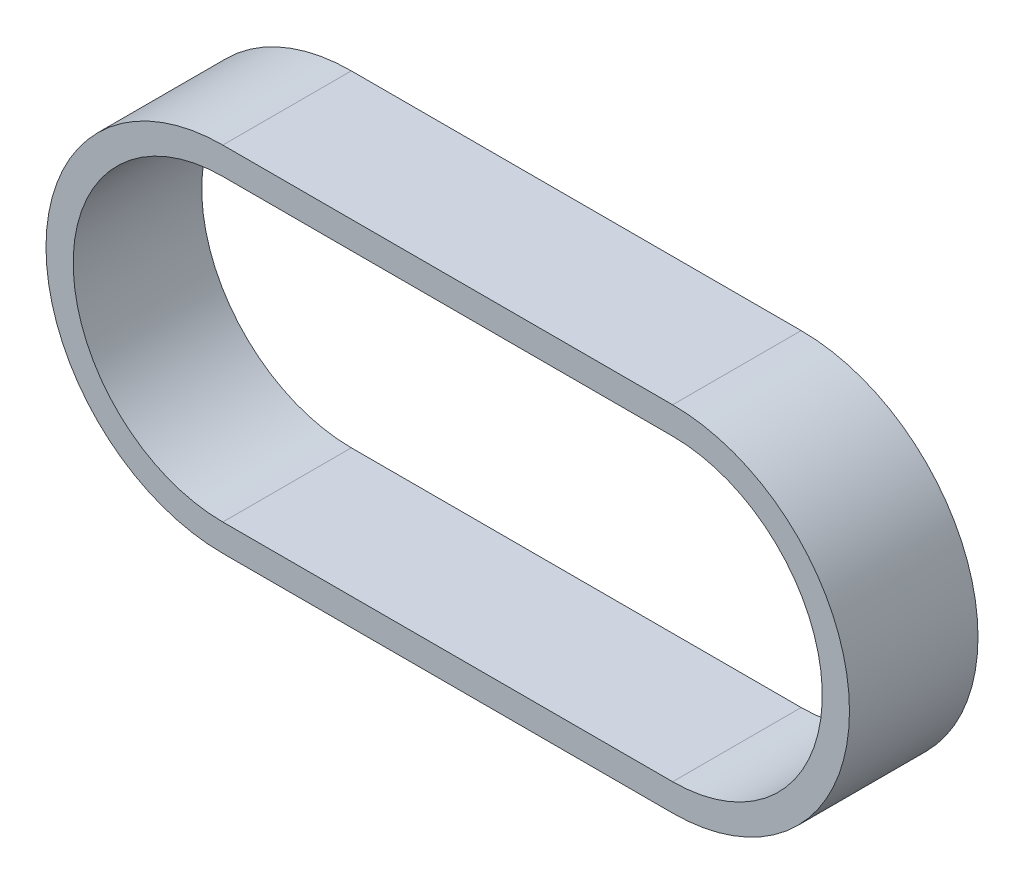
SolidWorks part; units mm, degrees
material "Rubber"
ref_plane "Front Plane" through (0, 0, 0) normal (0, 0, 1) x (1, 0, 0)
ref_plane "Top Plane" through (0, 0, 0) normal (0, 1, 0) x (1, 0, 0)
ref_plane "Right Plane" through (0, 0, 0) normal (1, 0, 0) x (0, 0, -1)
sketch "Sketch1" plane through (0, 0, 0) normal (0, 0, 1) x (1, 0, 0)
  line L0 (0, 20.6375) -> (52.5018, 20.6375)
  line L1 (0, 17.4625) -> (52.5018, 17.4625)
  line L2 (0, -17.4625) -> (52.5018, -17.4625)
  line L3 (0, -20.6375) -> (52.5018, -20.6375)
  arc A0 (0, 17.4625) -> (0, -17.4625) centre (0, 0) ccw
  arc A1 (0, 20.6375) -> (0, -20.6375) centre (0, 0) ccw
  arc A2 (52.5018, -20.6375) -> (52.5018, 20.6375) centre (52.5018, 0) ccw
  arc A3 (52.5018, -17.4625) -> (52.5018, 17.4625) centre (52.5018, 0) ccw
  dimension "D1" = 20.6375
  dimension "D2" = 17.4625
  dimension "D3" = 52.5018
extrude "Boss-Extrude1" add sketch "Sketch1" along normal blind 15
